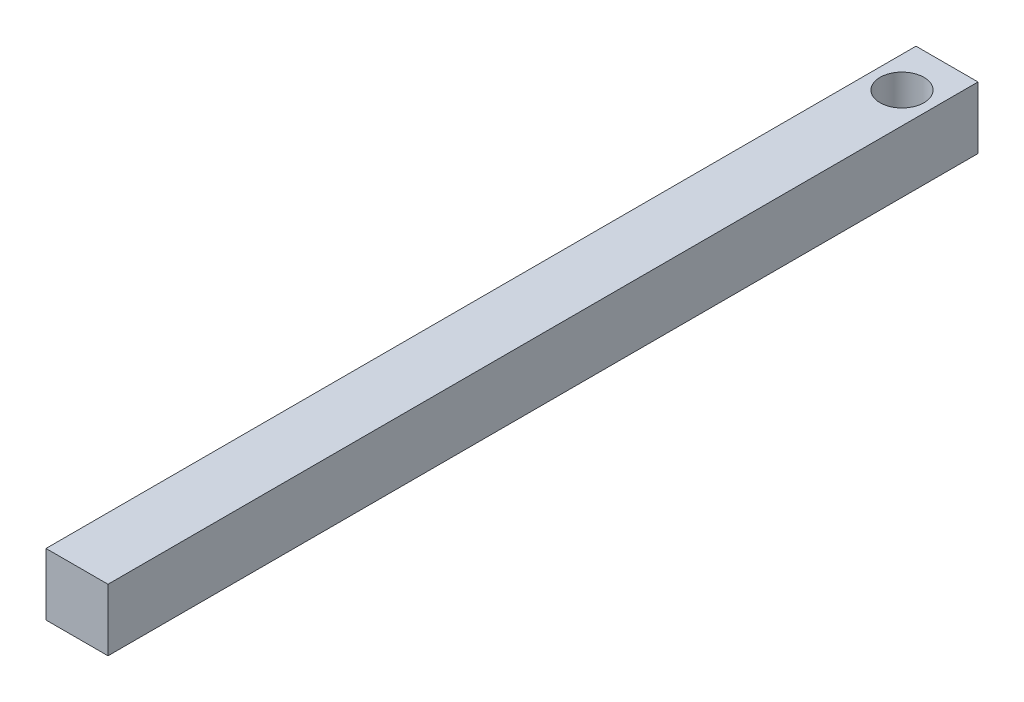
SolidWorks part; units mm, degrees
ref_plane "Front Plane" through (0, 0, 0) normal (0, 0, 1) x (1, 0, 0)
ref_plane "Top Plane" through (0, 0, 0) normal (0, 1, 0) x (1, 0, 0)
ref_plane "Right Plane" through (0, 0, 0) normal (1, 0, 0) x (0, 0, -1)
sketch "Sketch1" plane through (0, 0, 0) normal (0, 0, 1) x (1, 0, 0)
  line L1 (3.1, -3.1) -> (-3.1, -3.1)
  line L2 (3.1, -3.1) -> (3.1, 3.1)
  line L3 (3.1, 3.1) -> (-3.1, 3.1)
  line L4 (-3.1, -3.1) -> (-3.1, 3.1)
  line L5 (0, 3.1) -> (0, -3.1) construction
  line L6 (3.1, 0) -> (-3.1, 0) construction
  point P0 (0, 0)
  dimension "D1" = 6.2
  dimension "D2" = 6.2
extrude "Boss-Extrude1" add sketch "Sketch1" along normal blind 90
sketch "Sketch2" plane through (0, 3.1, 0) normal (0, 1, 0) x (1, 0, 0)
  line L0 (0, 0) -> (0, -15) construction
  line L1 (-3.1, -15) -> (3.1, -15) construction
  line L2 (-3.1, -3) -> (3.1, -3)
  line L4 (3.1, 0) -> (-3.1, 0)
  line L5 (-3.1, 0) -> (-3.1, -90)
  line L6 (-3.1, -90) -> (3.1, -90)
  line L7 (3.1, -90) -> (3.1, 0)
  line L8 (3.1, 0) -> (-3.1, 0)
  line L9 (-3.1, 0) -> (-3.1, -90)
  line L10 (-3.1, -90) -> (3.1, -90)
  line L11 (3.1, -90) -> (3.1, 0)
  circle A0 centre (0, -7.5) radius 2.2
  point P11 (0, -7.5)
  point P14 (0, -7.5)
  line M7 (3.1, 0) -> (-3.1, 0)
  line M8 (-3.1, 0) -> (-3.1, -90)
  line M10 (3.1, -90) -> (3.1, 0)
  dimension "D2" = 4.4
  dimension "D3" = 3
  dimension "D4" = 15
  dimension "D1" = 0
extrude "Cut-Extrude1" cut sketch "Sketch2" against normal blind 10 contours L2 M8 M10 M7 | A0
